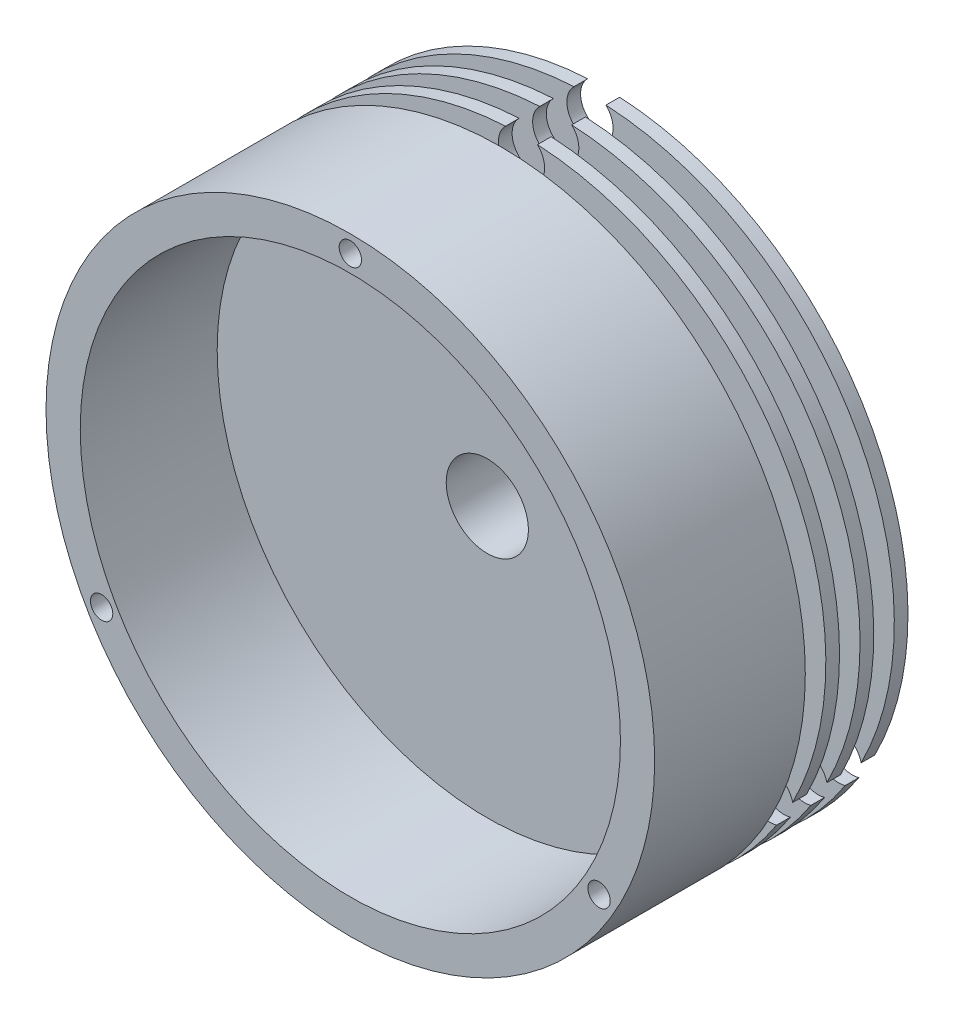
SolidWorks part; units mm, degrees
ref_plane "Plan de face" through (0, 0, 0) normal (0, 0, 1) x (1, 0, 0)
ref_plane "Plan de dessus" through (0, 0, 0) normal (0, 1, 0) x (1, 0, 0)
ref_plane "Plan de droite" through (0, 0, 0) normal (1, 0, 0) x (0, 0, -1)
sketch "Sketch1" plane through (0, 0, 0) normal (0, 0, 1) x (1, 0, 0)
  circle A0 centre (0, 0) radius 39.45
  circle A1 centre (0, 0) radius 44.45
extrude "Boss-Extrude1" add sketch "Sketch1" along normal blind 20
sketch "Sketch4" plane through (0, 0, 0) normal (0, 0, -1) x (-1, 0, 0)
  circle A0 centre (0, 0) radius 44.45
  circle A1 centre (0, 0) radius 6
extrude "Boss-Extrude2" add sketch "Sketch4" along normal blind 20
sketch "Sketch5" plane through (0, 0, -20) normal (0, 0, -1) x (-1, 0, 0)
  circle A0 centre (0, 0) radius 44.45
  circle A1 centre (0, 0) radius 33.45
extrude "Cut-Extrude1" cut sketch "Sketch5" against normal blind 3
pattern_linear "LPattern1" count 4 spacing 5 along (0, 0, 1) of "Cut-Extrude1"
sketch "Sketch13" plane through (0, 0, -17) normal (0, 0, -1) x (-1, 0, 0)
  line L0 (0, 44.45) -> (0, 39.45)
  circle A0 centre (0, 0) radius 44.45 construction
hole_wizard "CBORE for #4 Binding Head Machine Screw3" positions "Sketch14" profile "Sketch15" counterbore size "#4" standard "ANSI Inch" end condition through all
sketch "Sketch14" plane through (0, 0, -17) normal (0, 0, -1) x (-1, 0, 0)
  line L0 (0, 44.45) -> (0, 39.45) construction
  point P0 (0, 41.95)
sketch "Sketch15" plane through (0, 41.95, -17) normal (1, 0, 0) x (0, 1, 0)
  line L0 (0, 0) -> (0, 37)
  line L1 (0, 37) -> (1.6319, 37)
  line L3 (1.6319, 37) -> (1.6319, 14.4272)
  line L4 (1.6319, 14.4272) -> (3.3731, 14.4272)
  line L5 (3.3731, 14.4272) -> (3.3731, 0)
  line L7 (3.3731, 0) -> (0, 0)
  line L11 (0, -6.35) -> (0, 107.95) construction
  dimension "Thru Hole Dia." = 3.2639
  dimension "Thru Hole Depth" = 37
  dimension "C'Bore Dia." = 6.7462
  dimension "C'Bore Depth" = 14.4272
pattern_circular "CirPattern2" count 3 over 360 about axis through (0, 0, 0) along (0, 0, 1) of "CBORE for #4 Binding Head Machine Screw3"
